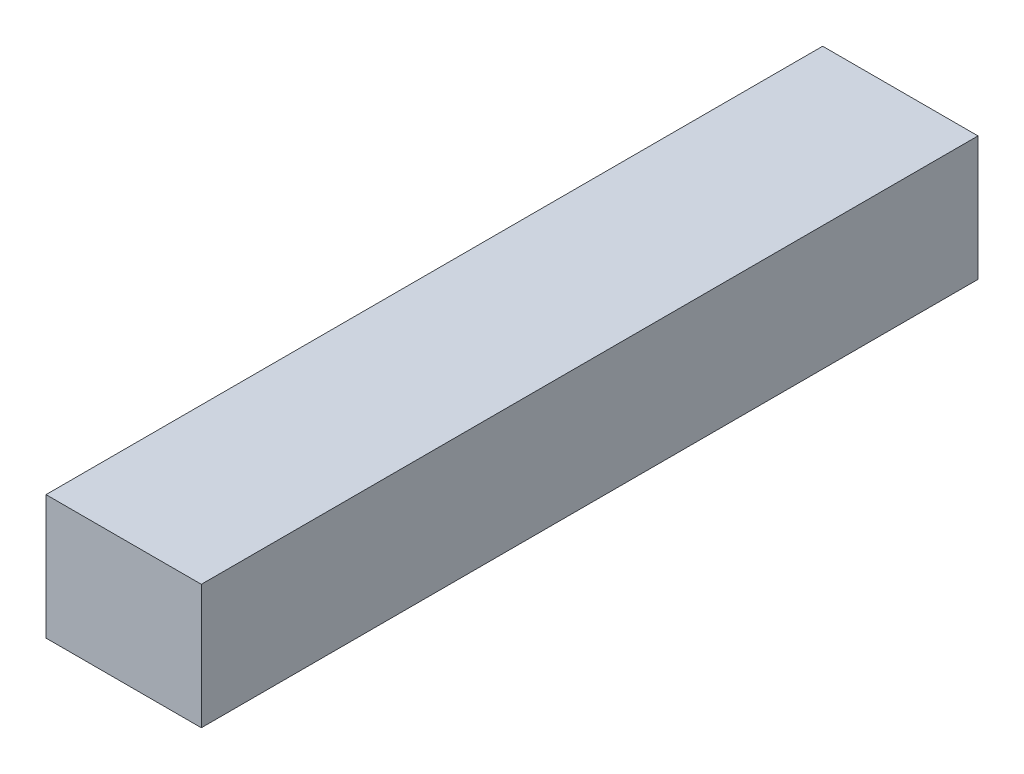
SolidWorks part; units mm, degrees
ref_plane "Front Plane" through (0, 0, 0) normal (0, 0, 1) x (1, 0, 0)
ref_plane "Top Plane" through (0, 0, 0) normal (0, 1, 0) x (1, 0, 0)
ref_plane "Right Plane" through (0, 0, 0) normal (1, 0, 0) x (0, 0, -1)
sketch "Sketch1" plane through (0, 0, 0) normal (0, 0, 1) x (1, 0, 0)
  line L1 (-3, -2.4) -> (3, -2.4)
  line L2 (-3, -2.4) -> (-3, 2.4)
  line L3 (-3, 2.4) -> (3, 2.4)
  line L4 (3, -2.4) -> (3, 2.4)
  line L5 (-3, -2.4) -> (3, 2.4) construction
  line L6 (-3, 2.4) -> (3, -2.4) construction
  point P0 (0, 0)
  dimension "D1" = 6
  dimension "D2" = 4.8
extrude "Boss-Extrude1" add sketch "Sketch1" against normal blind 30
